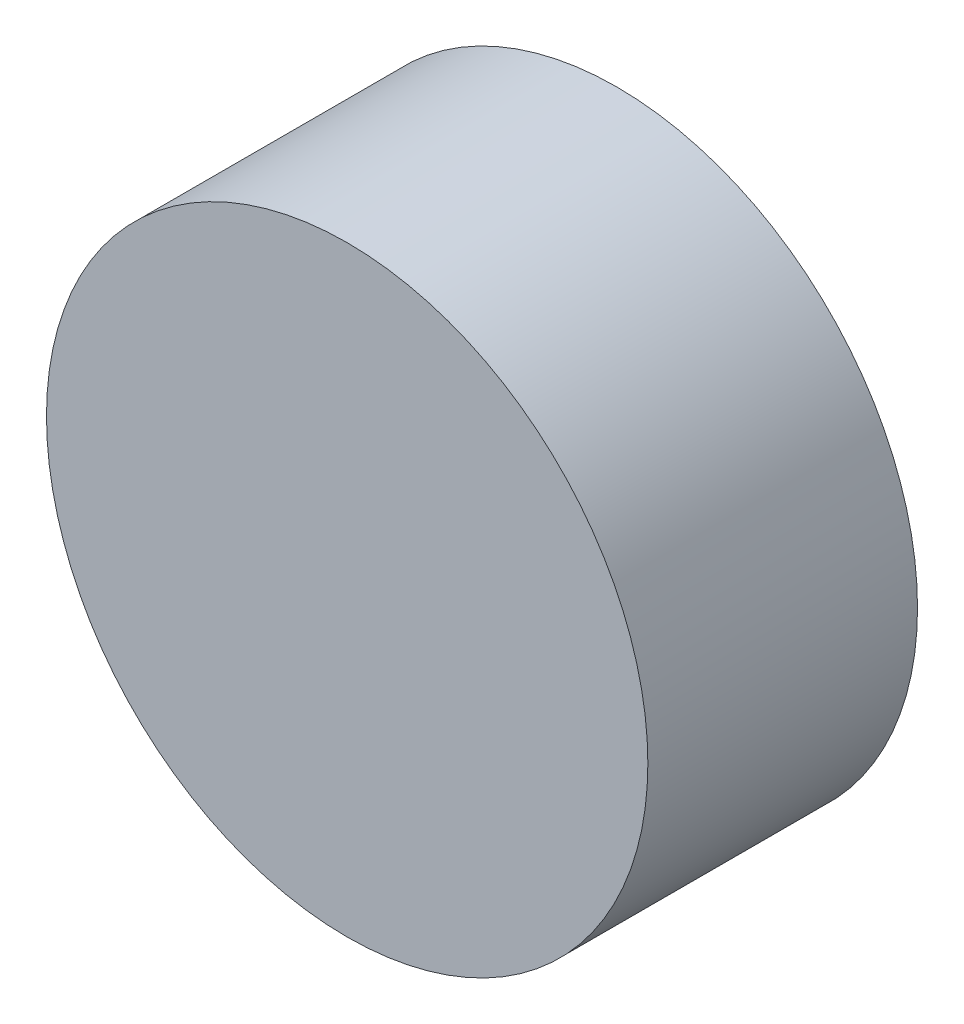
SolidWorks part; units mm, degrees
ref_plane "Plano frontal" through (0, 0, 0) normal (0, 0, 1) x (1, 0, 0)
ref_plane "Plano superior" through (0, 0, 0) normal (0, 1, 0) x (1, 0, 0)
ref_plane "Plano direito" through (0, 0, 0) normal (1, 0, 0) x (0, 0, -1)
sketch "Esboço1" plane through (0, 0, 0) normal (0, 0, 1) x (1, 0, 0)
  circle A0 centre (0, 0) radius 228.6
  point P3 (0, 0)
  point P8 (218.6, 0)
  point P18 (-30.5064, -62.7924)
extrude "Ressalto-extrusão3" add sketch "Esboço1" along normal blind 205 contours A0
sketch "Esboço5" plane through (0, 0, 0) normal (1, 0, 0) x (0, 0, -1)
  line L1 (0, 228.6) -> (-205, 228.6) construction
  line L2 (-200, 228.6) -> (-200, 228.5782)
  line L3 (-165, 193.5782) -> (-40, 193.5782)
  line L4 (-5, 228.5782) -> (-5, 228.6)
  arc A0 (-40, 193.5782) -> (-5, 228.5782) centre (-40, 228.5782) ccw
  arc A1 (-165, 193.5782) -> (-200, 228.5782) centre (-165, 228.5782) cw
  dimension "D3" = 35
